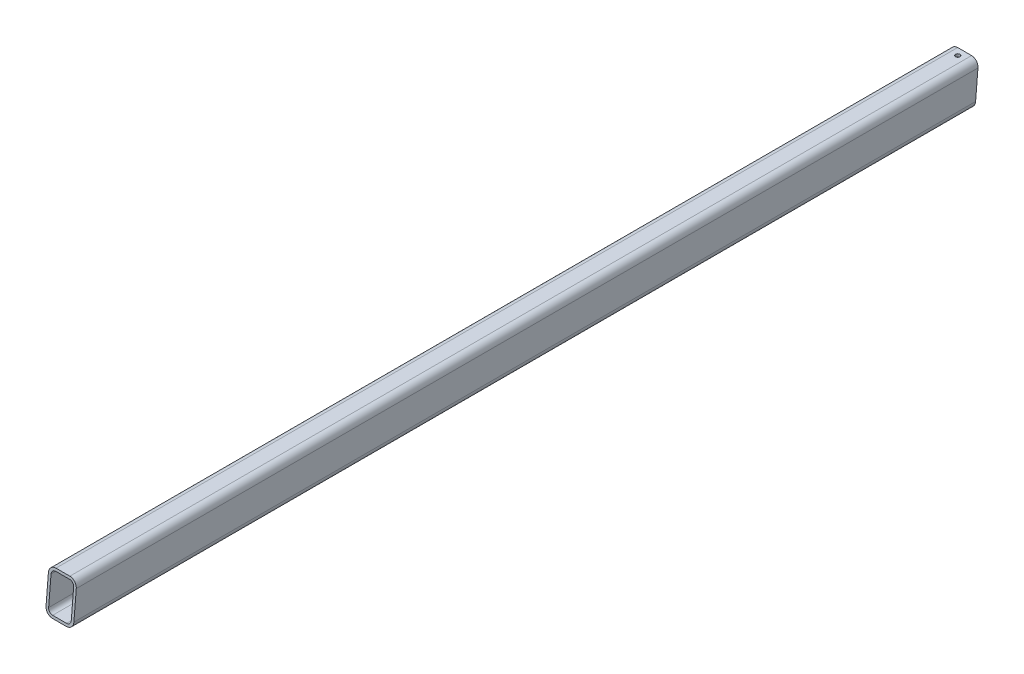
SolidWorks part; units mm, degrees
ref_plane "front" through (0, 0, 0) normal (0, 0, 1) x (1, 0, 0)
ref_plane "top" through (0, 0, 0) normal (0, 1, 0) x (1, 0, 0)
ref_plane "right" through (0, 0, 0) normal (1, 0, 0) x (0, 0, -1)
sketch "Sketch1" plane through (0, 0, 0) normal (0, 0, 1) x (1, 0, 0)
  line L0 (-20.6248, 25.4) -> (-20.6248, -25.4)
  line L1 (-12.7, 38.1) -> (12.7, 38.1)
  line L2 (-25.4, 25.4) -> (-25.4, -25.4)
  line L3 (-12.7, -38.1) -> (12.7, -38.1)
  line L4 (25.4, 25.4) -> (25.4, -25.4)
  line L5 (-12.7, -33.3248) -> (12.7, -33.3248)
  line L6 (20.6248, 25.4) -> (20.6248, -25.4)
  line L7 (-12.7, 33.3248) -> (12.7, 33.3248)
  arc A0 (25.4, 25.4) -> (12.7, 38.1) centre (12.7, 25.4) ccw
  arc A1 (25.4, -25.4) -> (12.7, -38.1) centre (12.7, -25.4) cw
  arc A2 (-12.7, -38.1) -> (-25.4, -25.4) centre (-12.7, -25.4) cw
  arc A3 (-25.4, 25.4) -> (-12.7, 38.1) centre (-12.7, 25.4) cw
  arc A4 (-12.7, -33.3248) -> (-20.6248, -25.4) centre (-12.7, -25.4) cw
  arc A5 (20.6248, -25.4) -> (12.7, -33.3248) centre (12.7, -25.4) cw
  arc A6 (20.6248, 25.4) -> (12.7, 33.3248) centre (12.7, 25.4) ccw
  arc A7 (-20.6248, 25.4) -> (-12.7, 33.3248) centre (-12.7, 25.4) cw
  point P4 (0, 38.1)
  point P5 (25.4, 0)
  dimension "D1" = 12.7
  dimension "D2" = 76.2
  dimension "D3" = 50.8
  dimension "D4" = 4.7752
extrude "Base-Extrude" add sketch "Sketch1" along normal mid plane 1676.4
sketch "Sketch2" plane through (0, 0, 0) normal (1, 0, 0) x (0, 0, -1)
  line L0 (-811.7952, 121.1135) -> (-832.4502, -121.1135)
  line L2 (833.1223, 128.995) -> (811.1231, -128.995)
  line L4 (-811.7952, 121.1135) -> (-857.8502, 121.1135)
  line L5 (-857.8502, 121.1135) -> (-857.8502, -121.1135)
  line L6 (858.5223, 128.995) -> (858.5223, -128.995)
  line L7 (858.5223, -128.995) -> (811.1231, -128.995)
  line L8 (-832.4502, -121.1135) -> (-857.8502, -121.1135)
  line L9 (0, 0) -> (-816.188, 69.5974) construction
  line L10 (858.5223, 128.995) -> (833.1223, 128.995)
  line L12 (0, 0) -> (816.188, -69.5974) construction
  line L13 (-816.188, 69.5974) -> (828.0574, 69.5974) construction
  point P5 (822.1227, 0)
  point P6 (-822.1227, 0)
  dimension "D1" = 4.874
  dimension "D2" = 139.7
  dimension "D3" = 25.4
  dimension "D4" = 25.4
  dimension "D5" = 1638.3
extrude "Cut-Extrude1" cut sketch "Sketch2" against normal mid plane 76.2
sketch "Sketch3" plane through (0, 0, 0) normal (1, 0, 0) x (0, 0, -1)
  line L0 (-822.1227, 0) -> (822.1227, 0) construction
  line L1 (819.9568, -25.4) -> (824.2886, 25.4) construction
  line L2 (-822.1227, 0) -> (-745.3908, -6.543) construction
  line L3 (-819.9568, 25.4) -> (-824.2886, -25.4) construction
  line L4 (-822.1227, 0) -> (-840.1744, 0) construction
  dimension "D1" = 1644.2454
ref_plane "Plane1" through (0, 0, 822.1227) normal (0, -0.085, -0.9964) x (-1, 0, 0)
sketch "Sketch4" plane through (0, 0, 0) normal (0, 1, 0) x (1, 0, 0)
  line L0 (12.7, -825.3715) -> (-12.7, -825.3715) construction
  circle A0 centre (0, -255.4971) radius 2.7051
  dimension "D2" = 5.4102
  dimension "D1" = 569.8744
extrude "Cut-Extrude2" [suppressed] cut sketch "Sketch4" against normal through all
sketch "Sketch5" plane through (0, 0, 0) normal (0, 1, 0) x (1, 0, 0)
  circle A0 centre (0, 806.45) radius 3.9751
  dimension "D2" = 7.9502
  dimension "D1" = 806.45
extrude "Cut-Extrude3" cut sketch "Sketch5" against normal through all
sketch "Sketch6" plane through (0, 0, 0) normal (0, 1, 0) x (1, 0, 0)
  circle A0 centre (0, 812.8) radius 3.9751
  dimension "D2" = 7.9502
  dimension "D1" = 812.8
extrude "Cut-Extrude4" cut sketch "Sketch6" along normal through all
sketch "Sketch7" [suppressed] plane through (0, 0, 0) normal (0, 1, 0) x (1, 0, 0)
  line L1 (-101.7926, 773.8548) -> (117.9868, 773.8548)
  line L2 (-101.7926, 773.8548) -> (-101.7926, -903.409)
  line L3 (-101.7926, -903.409) -> (117.9868, -903.409)
  line L4 (117.9868, 773.8548) -> (117.9868, -903.409)
extrude "Cut-Extrude5" [suppressed] cut sketch "Sketch7" against normal mid plane 127
sketch "locate" plane through (-25.4, 0, 0) normal (-1, 0, 0) x (0, 0, 1)
  point P0 (0, 0)
